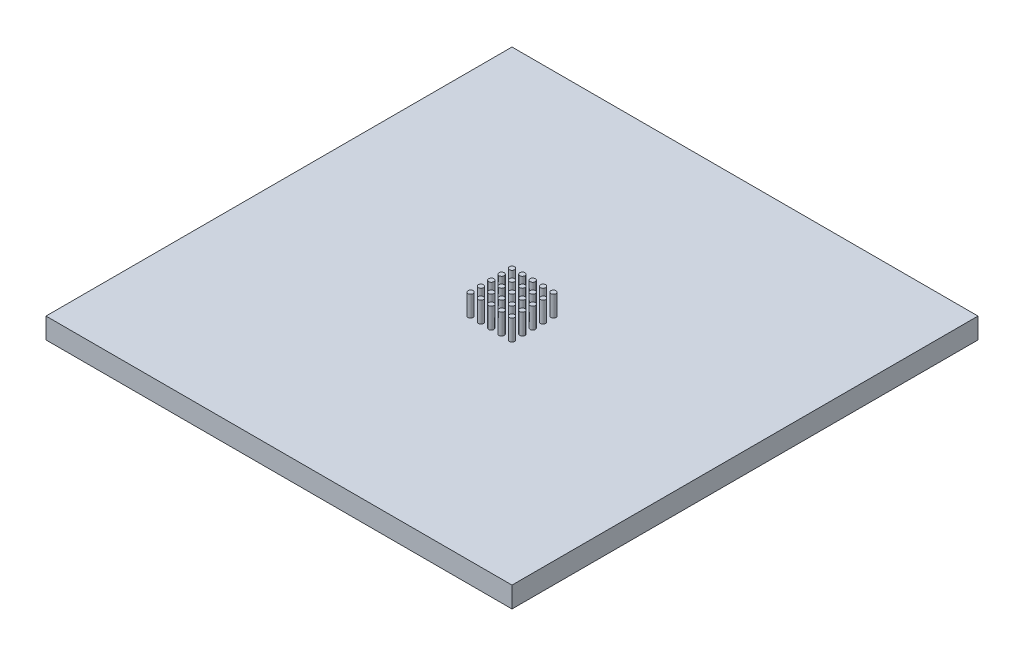
SolidWorks part; units mm, degrees
ref_plane "Front Plane" through (0, 0, 0) normal (0, 0, 1) x (1, 0, 0)
ref_plane "Top Plane" through (0, 0, 0) normal (0, 1, 0) x (1, 0, 0)
ref_plane "Right Plane" through (0, 0, 0) normal (1, 0, 0) x (0, 0, -1)
sketch "Sketch1" plane through (0, 0, 0) normal (0, 1, 0) x (1, 0, 0)
  line L1 (-22.5, 22.5) -> (22.5, 22.5)
  line L2 (-22.5, 22.5) -> (-22.5, -22.5)
  line L3 (-22.5, -22.5) -> (22.5, -22.5)
  line L4 (22.5, 22.5) -> (22.5, -22.5)
  dimension "D1" = 45
  dimension "D2" = 45
  dimension "D3" = 22.5
  dimension "D4" = 22.5
extrude "Baseplate" add sketch "Sketch1" along normal blind 2
sketch "Sketch2" plane through (0, 2, 0) normal (0, 1, 0) x (1, 0, 0)
  circle A1 centre (-2, -2) radius 0.25
  point P2 (0, 0)
  point P4 (0, 0)
  point P5 (0, 0)
  point P6 (0, 0)
  point P8 (-8.505, 0.4737)
  point P9 (0, 0)
  point P10 (0, 0)
extrude "Pinfin" add sketch "Sketch2" along normal blind 2 contours A1
pattern_linear "Pinfin Pattern" count 5 spacing 1 along (0, 0, -1) count 5 spacing 1 along (1, 0, 0) of "Pinfin"
equation "\"d\"= 0.5mm"
equation "\"p\"= 1.0mm"
equation "\"h\"= 2.0mm"
equation "\"n\"= 5.0mm"
equation "\"D1@Pinfin\"=\"h\""
equation "\"D4@Pinfin Pattern\"=\"p\""
equation "\"D3@Pinfin Pattern\"=\"p\""
equation "\"D2@Pinfin Pattern\"=\"n\""
equation "\"D1@Pinfin Pattern\"=\"n\""
equation "\"D1@Baseplate\"=\"h\""
